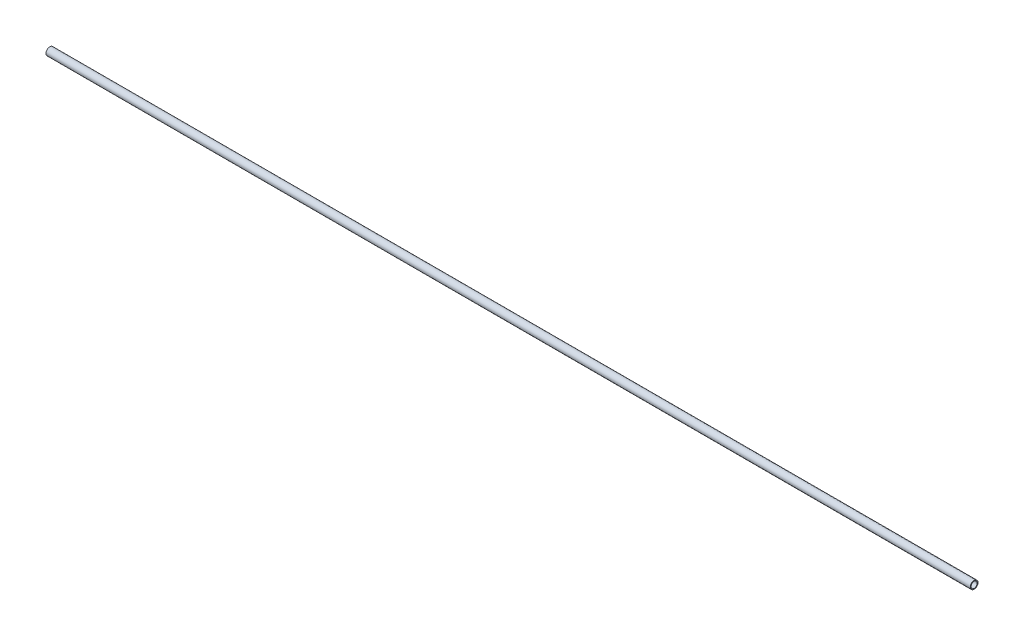
SolidWorks part; units mm, degrees
material "Thornel Mat VMA"
ref_plane "Front" through (0, 0, 0) normal (0, 0, 1) x (1, 0, 0)
ref_plane "Top" through (0, 0, 0) normal (0, 1, 0) x (1, 0, 0)
ref_plane "Right" through (0, 0, 0) normal (1, 0, 0) x (0, 0, -1)
sketch "Sketch1" plane through (0, 0, 0) normal (1, 0, 0) x (0, 0, -1)
  circle A0 centre (0, 0) radius 5.08
  circle A1 centre (0, 0) radius 6.35
  dimension "D1" = 10.16
  dimension "D2" = 12.7
extrude "Boss-Extrude1" add sketch "Sketch1" along normal blind 1524 contours A0
